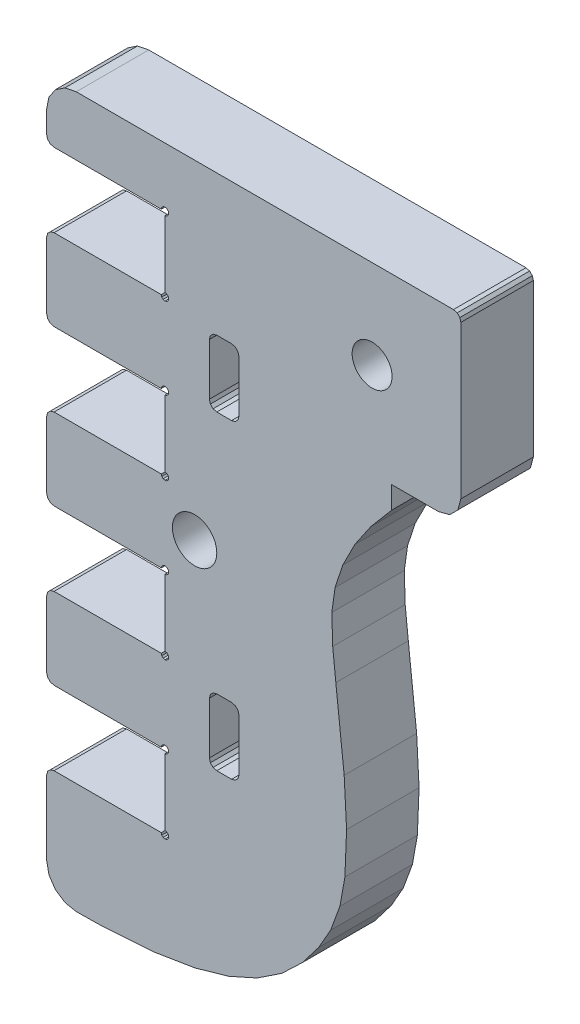
SolidWorks part; units mm, degrees
ref_plane "Plan de face" through (0, 0, 0) normal (0, 0, 1) x (1, 0, 0)
ref_plane "Plan de dessus" through (0, 0, 0) normal (0, 1, 0) x (1, 0, 0)
ref_plane "Plan de droite" through (0, 0, 0) normal (1, 0, 0) x (0, 0, -1)
ref_plane "Plan1" through (0, 0, 377.0447) normal (0, 0, 1) x (1, 0, 0)
sketch "Esquisse1" plane through (0, 0, 377.0447) normal (0, 0, 1) x (1, 0, 0)
  line L0 (15.8912, 3.3305) -> (17.2951, 4.667)
  line L1 (17.2951, 4.667) -> (18.3971, 6.111)
  line L2 (18.3971, 6.111) -> (19.1985, 7.5157)
  line L3 (19.1985, 7.5157) -> (19.8294, 9.236)
  line L4 (19.8294, 9.236) -> (20.1607, 11.1078)
  line L5 (20.1607, 11.1078) -> (20.2751, 13.9448)
  line L6 (20.2751, 13.9448) -> (20.1117, 17.0383)
  line L7 (20.1117, 17.0383) -> (19.5481, 22.1817)
  line L8 (19.5481, 22.1817) -> (19.3368, 24.1934)
  line L9 (19.3368, 24.1934) -> (19.2774, 26.1578)
  line L10 (19.2774, 26.1578) -> (19.4976, 27.7229)
  line L11 (19.4976, 27.7229) -> (20.0152, 29.3005)
  line L12 (20.0152, 29.3005) -> (20.8426, 30.9281)
  line L13 (20.8426, 30.9281) -> (21.9164, 32.5048)
  line L14 (21.9164, 32.5048) -> (23.3235, 34.1655)
  line L15 (23.3235, 34.1655) -> (23.3235, 35.6655)
  line L16 (23.3235, 35.6655) -> (26.5, 35.6655)
  line L17 (26.5, 35.6655) -> (27.25, 35.8665)
  line L18 (27.25, 35.8665) -> (27.799, 36.4155)
  line L19 (27.799, 36.4155) -> (28, 37.1655)
  line L20 (28, 37.1655) -> (28, 47.5)
  line L21 (28, 47.5) -> (27.933, 47.75)
  line L22 (27.933, 47.75) -> (27.75, 47.933)
  line L23 (27.75, 47.933) -> (27.5, 48)
  line L24 (27.5, 48) -> (2, 48)
  line L25 (2, 48) -> (1.2346, 47.8477)
  line L26 (1.2346, 47.8477) -> (0.5858, 47.4142)
  line L27 (0.5858, 47.4142) -> (0.1522, 46.7654)
  line L28 (0.1522, 46.7654) -> (0, 46)
  line L29 (0, 46) -> (0, 44.5)
  line L30 (0, 44.5) -> (0.067, 44.25)
  line L31 (0.067, 44.25) -> (0.25, 44.067)
  line L32 (0.25, 44.067) -> (0.5, 44)
  line L33 (0.5, 44) -> (7.75, 44)
  line L34 (7.75, 44) -> (7.7835, 44.125)
  line L35 (7.7835, 44.125) -> (7.875, 44.2165)
  line L36 (7.875, 44.2165) -> (8, 44.25)
  line L37 (8, 44.25) -> (8.125, 44.2165)
  line L38 (8.125, 44.2165) -> (8.2165, 44.125)
  line L39 (8.2165, 44.125) -> (8.25, 44)
  line L40 (8.25, 44) -> (8.2165, 43.875)
  line L41 (8.2165, 43.875) -> (8.125, 43.7835)
  line L42 (8.125, 43.7835) -> (8, 43.75)
  line L43 (8, 43.75) -> (8, 39.25)
  line L44 (8, 39.25) -> (8.125, 39.2165)
  line L45 (8.125, 39.2165) -> (8.2165, 39.125)
  line L46 (8.2165, 39.125) -> (8.25, 39)
  line L47 (8.25, 39) -> (8.2165, 38.875)
  line L48 (8.2165, 38.875) -> (8.125, 38.7835)
  line L49 (8.125, 38.7835) -> (8, 38.75)
  line L50 (8, 38.75) -> (7.875, 38.7835)
  line L51 (7.875, 38.7835) -> (7.7835, 38.875)
  line L52 (7.7835, 38.875) -> (7.75, 39)
  line L53 (7.75, 39) -> (0.5, 39)
  line L54 (0.5, 39) -> (0.25, 38.933)
  line L55 (0.25, 38.933) -> (0.067, 38.75)
  line L56 (0.067, 38.75) -> (0, 38.5)
  line L57 (0, 38.5) -> (0, 34)
  line L58 (0, 34) -> (0.067, 33.75)
  line L59 (0.067, 33.75) -> (0.25, 33.567)
  line L60 (0.25, 33.567) -> (0.5, 33.5)
  line L61 (0.5, 33.5) -> (7.75, 33.5)
  line L62 (7.75, 33.5) -> (7.7835, 33.625)
  line L63 (7.7835, 33.625) -> (7.875, 33.7165)
  line L64 (7.875, 33.7165) -> (8, 33.75)
  line L65 (8, 33.75) -> (8.125, 33.7165)
  line L66 (8.125, 33.7165) -> (8.2165, 33.625)
  line L67 (8.2165, 33.625) -> (8.25, 33.5)
  line L68 (8.25, 33.5) -> (8.2165, 33.375)
  line L69 (8.2165, 33.375) -> (8.125, 33.2835)
  line L70 (8.125, 33.2835) -> (8, 33.25)
  line L71 (8, 33.25) -> (8, 28.75)
  line L72 (8, 28.75) -> (8.125, 28.7165)
  line L73 (8.125, 28.7165) -> (8.2165, 28.625)
  line L74 (8.2165, 28.625) -> (8.25, 28.5)
  line L75 (8.25, 28.5) -> (8.2165, 28.375)
  line L76 (8.2165, 28.375) -> (8.125, 28.2835)
  line L77 (8.125, 28.2835) -> (8, 28.25)
  line L78 (8, 28.25) -> (7.875, 28.2835)
  line L79 (7.875, 28.2835) -> (7.7835, 28.375)
  line L80 (7.7835, 28.375) -> (7.75, 28.5)
  line L81 (7.75, 28.5) -> (0.5, 28.5)
  line L82 (0.5, 28.5) -> (0.25, 28.433)
  line L83 (0.25, 28.433) -> (0.067, 28.25)
  line L84 (0.067, 28.25) -> (0, 28)
  line L85 (0, 28) -> (0, 23.5)
  line L86 (0, 23.5) -> (0.067, 23.25)
  line L87 (0.067, 23.25) -> (0.25, 23.067)
  line L88 (0.25, 23.067) -> (0.5, 23)
  line L89 (0.5, 23) -> (7.75, 23)
  line L90 (7.75, 23) -> (7.7835, 23.125)
  line L91 (7.7835, 23.125) -> (7.875, 23.2165)
  line L92 (7.875, 23.2165) -> (8, 23.25)
  line L93 (8, 23.25) -> (8.125, 23.2165)
  line L94 (8.125, 23.2165) -> (8.2165, 23.125)
  line L95 (8.2165, 23.125) -> (8.25, 23)
  line L96 (8.25, 23) -> (8.2165, 22.875)
  line L97 (8.2165, 22.875) -> (8.125, 22.7835)
  line L98 (8.125, 22.7835) -> (8, 22.75)
  line L99 (8, 22.75) -> (8, 18.25)
  line L100 (8, 18.25) -> (8.125, 18.2165)
  line L101 (8.125, 18.2165) -> (8.2165, 18.125)
  line L102 (8.2165, 18.125) -> (8.25, 18)
  line L103 (8.25, 18) -> (8.2165, 17.875)
  line L104 (8.2165, 17.875) -> (8.125, 17.7835)
  line L105 (8.125, 17.7835) -> (8, 17.75)
  line L106 (8, 17.75) -> (7.875, 17.7835)
  line L107 (7.875, 17.7835) -> (7.7835, 17.875)
  line L108 (7.7835, 17.875) -> (7.75, 18)
  line L109 (7.75, 18) -> (0.5, 18)
  line L110 (0.5, 18) -> (0.25, 17.933)
  line L111 (0.25, 17.933) -> (0.067, 17.75)
  line L112 (0.067, 17.75) -> (0, 17.5)
  line L113 (0, 17.5) -> (0, 13)
  line L114 (0, 13) -> (0.067, 12.75)
  line L115 (0.067, 12.75) -> (0.25, 12.567)
  line L116 (0.25, 12.567) -> (0.5, 12.5)
  line L117 (0.5, 12.5) -> (7.75, 12.5)
  line L118 (7.75, 12.5) -> (7.7835, 12.625)
  line L119 (7.7835, 12.625) -> (7.875, 12.7165)
  line L120 (7.875, 12.7165) -> (8, 12.75)
  line L121 (8, 12.75) -> (8.125, 12.7165)
  line L122 (8.125, 12.7165) -> (8.2165, 12.625)
  line L123 (8.2165, 12.625) -> (8.25, 12.5)
  line L124 (8.25, 12.5) -> (8.2165, 12.375)
  line L125 (8.2165, 12.375) -> (8.125, 12.2835)
  line L126 (8.125, 12.2835) -> (8, 12.25)
  line L127 (8, 12.25) -> (8, 7.75)
  line L128 (8, 7.75) -> (8.125, 7.7165)
  line L129 (8.125, 7.7165) -> (8.2165, 7.625)
  line L130 (8.2165, 7.625) -> (8.25, 7.5)
  line L131 (8.25, 7.5) -> (8.2165, 7.375)
  line L132 (8.2165, 7.375) -> (8.125, 7.2835)
  line L133 (8.125, 7.2835) -> (8, 7.25)
  line L134 (8, 7.25) -> (7.875, 7.2835)
  line L135 (7.875, 7.2835) -> (7.7835, 7.375)
  line L136 (7.7835, 7.375) -> (7.75, 7.5)
  line L137 (7.75, 7.5) -> (0.5, 7.5)
  line L138 (0.5, 7.5) -> (0.25, 7.433)
  line L139 (0.25, 7.433) -> (0.067, 7.25)
  line L140 (0.067, 7.25) -> (0, 7)
  line L141 (0, 7) -> (0, 2)
  line L142 (0, 2) -> (0.1522, 1.2346)
  line L143 (0.1522, 1.2346) -> (0.5858, 0.5858)
  line L144 (0.5858, 0.5858) -> (1.2346, 0.1522)
  line L145 (1.2346, 0.1522) -> (2, 0)
  line L146 (2, 0) -> (3.7765, 0.0255)
  line L147 (3.7765, 0.0255) -> (7.2484, 0.2625)
  line L148 (7.2484, 0.2625) -> (10.0367, 0.7181)
  line L149 (10.0367, 0.7181) -> (12.3217, 1.3736)
  line L150 (12.3217, 1.3736) -> (14.2385, 2.2332)
  line L151 (14.2385, 2.2332) -> (15.8912, 3.3305)
  line L152 (12.933, 13.25) -> (12.75, 13.067)
  line L153 (12.75, 13.067) -> (12.5, 13)
  line L154 (12.5, 13) -> (11.5, 13)
  line L155 (11.5, 13) -> (11.25, 13.067)
  line L156 (11.25, 13.067) -> (11.067, 13.25)
  line L157 (11.067, 13.25) -> (11, 13.5)
  line L158 (11, 13.5) -> (11, 17)
  line L159 (11, 17) -> (11.067, 17.25)
  line L160 (11.067, 17.25) -> (11.25, 17.433)
  line L161 (11.25, 17.433) -> (11.5, 17.5)
  line L162 (11.5, 17.5) -> (12.5, 17.5)
  line L163 (12.5, 17.5) -> (12.75, 17.433)
  line L164 (12.75, 17.433) -> (12.933, 17.25)
  line L165 (12.933, 17.25) -> (13, 17)
  line L166 (13, 17) -> (13, 13.5)
  line L167 (13, 13.5) -> (12.933, 13.25)
  line L192 (11.25, 34.067) -> (11.067, 34.25)
  line L193 (11.067, 34.25) -> (11, 34.5)
  line L194 (11, 34.5) -> (11, 38)
  line L195 (11, 38) -> (11.067, 38.25)
  line L196 (11.067, 38.25) -> (11.25, 38.433)
  line L197 (11.25, 38.433) -> (11.5, 38.5)
  line L198 (11.5, 38.5) -> (12.5, 38.5)
  line L199 (12.5, 38.5) -> (12.75, 38.433)
  line L200 (12.75, 38.433) -> (12.933, 38.25)
  line L201 (12.933, 38.25) -> (13, 38)
  line L202 (13, 38) -> (13, 34.5)
  line L203 (13, 34.5) -> (12.933, 34.25)
  line L204 (12.933, 34.25) -> (12.75, 34.067)
  line L205 (12.75, 34.067) -> (12.5, 34)
  line L206 (12.5, 34) -> (11.5, 34)
  line L207 (11.5, 34) -> (11.25, 34.067)
  circle A0 centre (22, 42) radius 1.35
  circle A1 centre (10, 25.75) radius 1.5
  dimension "D1" = 2.7
  dimension "D2" = 3
extrude "Boss.-Extru.1" add sketch "Esquisse1" against normal blind 4.9
